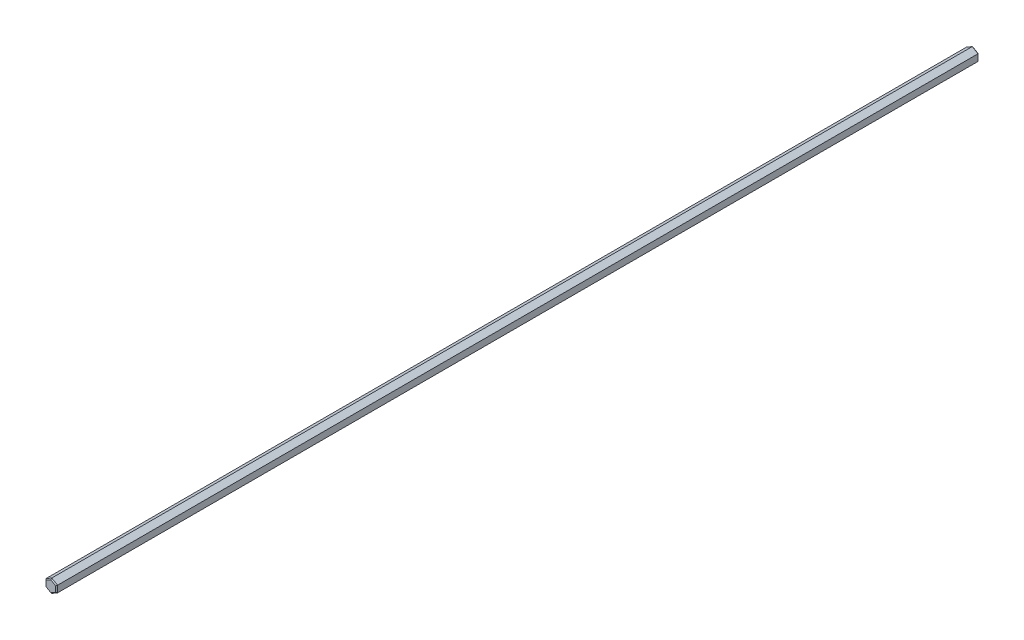
SolidWorks part; units mm, degrees
ref_plane "Front Plane" through (0, 0, 0) normal (0, 0, 1) x (1, 0, 0)
ref_plane "Top Plane" through (0, 0, 0) normal (0, 1, 0) x (1, 0, 0)
ref_plane "Right Plane" through (0, 0, 0) normal (1, 0, 0) x (0, 0, -1)
ref_plane "Plane1" through (0, 0, 355) normal (0, 0, 1) x (1, 0, 0)
sketch "Sketch1" plane through (0, 0, 355) normal (0, 0, 1) x (1, 0, 0)
  line L0 (0, -2.8868) -> (2.5, -1.4434)
  line L1 (2.5, -1.4434) -> (2.5, 1.4434)
  line L2 (2.5, 1.4434) -> (0, 2.8868)
  line L3 (0, 2.8868) -> (-2.5, 1.4434)
  line L4 (-2.5, 1.4434) -> (-2.5, -1.4434)
  line L5 (-2.5, -1.4434) -> (0, -2.8868)
extrude "Boss-Extrude1" add sketch "Sketch1" against normal blind 400
chamfer "Chamfer1" distance 0.4 angle 45 12 edges at (-2.5, 0, -45) (-1.25, 2.1651, -45) (-1.25, -2.1651, -45) (1.25, 2.1651, -45) (1.25, -2.1651, -45) (2.5, 0, -45) (-1.25, 2.1651, 355) (1.25, 2.1651, 355) (-2.5, 0, 355) (2.5, 0, 355) (-1.25, -2.1651, 355) (1.25, -2.1651, 355)
